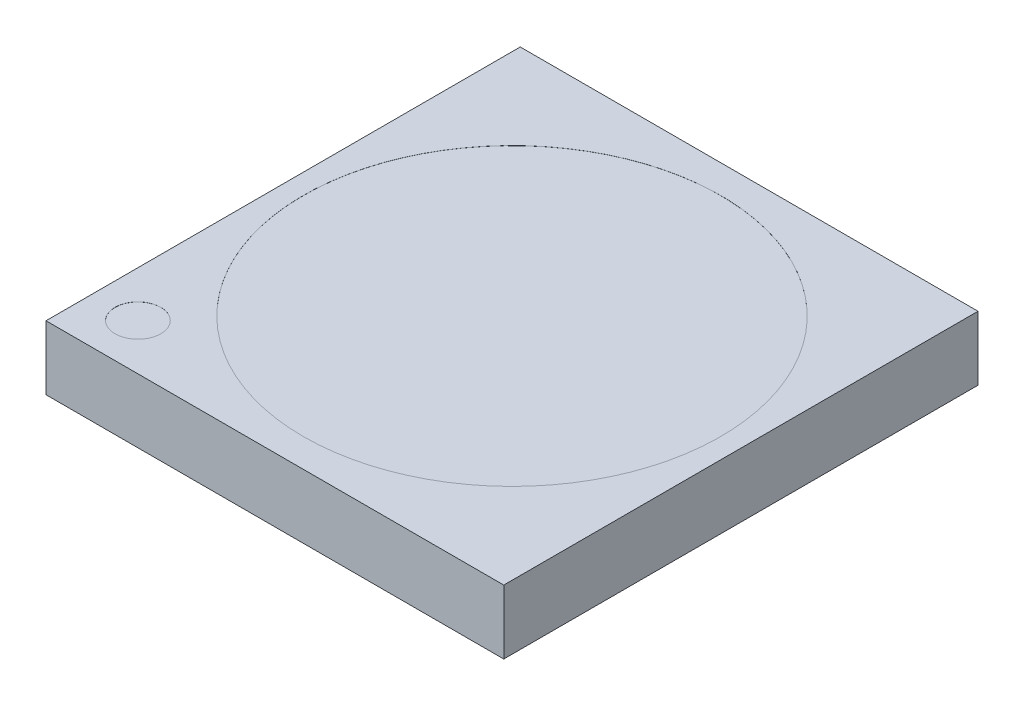
SolidWorks part; units mm, degrees
ref_plane "Alzado" through (0, 0, 0) normal (0, 0, 1) x (1, 0, 0)
ref_plane "Planta" through (0, 0, 0) normal (0, 1, 0) x (1, 0, 0)
ref_plane "Vista lateral" through (0, 0, 0) normal (1, 0, 0) x (0, 0, -1)
ref_plane "Plane1" through (0, 0, 0) normal (0, -1, 0) x (1, 0, 0)
sketch "Sketch1" plane through (0, 0, 0) normal (0, -1, 0) x (1, 0, 0)
  line L0 (2.5, 2.59) -> (-2.5, 2.59)
  line L1 (-2.5, 2.59) -> (-2.5, -2.59)
  line L2 (-2.5, -2.59) -> (2.5, -2.59)
  line L3 (2.5, -2.59) -> (2.5, 2.59)
extrude "Extrude1" add sketch "Sketch1" against normal blind 0.7
sketch "Sketch2" plane through (0, 0, 0) normal (0, -1, 0) x (1, 0, 0)
  line L0 (-0.3, 0.18) -> (-0.3, 2.27)
  line L1 (-0.3, 2.27) -> (-1.3472, 2.27)
  line L2 (-2.1, 1.4301) -> (-2.1, -1.4301)
  line L3 (-1.3472, -2.27) -> (-0.3, -2.27)
  line L4 (-0.3, -2.27) -> (-0.3, -0.18)
  arc A0 (-0.3, -0.18) -> (-0.3, 0.18) centre (-0.3, 0) cw
  arc A1 (-1.3472, 2.27) -> (-1.5249, 2.0616) centre (-1.3472, 2.09) ccw
  arc A2 (-1.5249, 2.0616) -> (-1.9168, 1.6101) centre (-1.91, 2) cw
  arc A3 (-1.9168, 1.6101) -> (-2.1, 1.4301) centre (-1.92, 1.4301) ccw
  arc A4 (-2.1, -1.4301) -> (-1.92, -1.6101) centre (-1.92, -1.4301) ccw
  arc A5 (-1.92, -1.6101) -> (-1.9168, -1.6101) centre (-1.92, -1.4301) ccw
  arc A6 (-1.9168, -1.6101) -> (-1.5249, -2.0616) centre (-1.91, -2) cw
  arc A7 (-1.5249, -2.0616) -> (-1.3472, -2.27) centre (-1.3472, -2.09) ccw
extrude "Extrude2" cut sketch "Sketch2" against normal blind 0.001
sketch "Sketch3" plane through (0, 0, 0) normal (0, -1, 0) x (1, 0, 0)
  line L0 (1.3472, 2.27) -> (0.3, 2.27)
  line L1 (0.3, 2.27) -> (0.3, -2.27)
  line L2 (0.3, -2.27) -> (1.3472, -2.27)
  line L3 (2.1, -1.4301) -> (2.1, 1.4301)
  arc A0 (1.9168, 1.6101) -> (1.5249, 2.0616) centre (1.91, 2) cw
  arc A1 (1.5249, 2.0616) -> (1.3472, 2.27) centre (1.3472, 2.09) ccw
  arc A2 (1.3472, -2.27) -> (1.5249, -2.0616) centre (1.3472, -2.09) ccw
  arc A3 (1.5249, -2.0616) -> (1.9168, -1.6101) centre (1.91, -2) cw
  arc A4 (1.9168, -1.6101) -> (1.92, -1.6101) centre (1.92, -1.4301) ccw
  arc A5 (1.92, -1.6101) -> (2.1, -1.4301) centre (1.92, -1.4301) ccw
  arc A6 (2.1, 1.4301) -> (1.9168, 1.6101) centre (1.92, 1.4301) ccw
extrude "Extrude3" cut sketch "Sketch3" against normal blind 0.001
ref_plane "Plane2" through (0, 0, 0) normal (0, 0, -1) x (-1, 0, 0)
sketch "Sketch4" plane through (0, 0, 0) normal (0, 0, -1) x (-1, 0, 0)
  line L0 (-2.28, 0.699) -> (0, 0.699)
  line L1 (0, 0.699) -> (0, 0.7)
  line L2 (0, 0.7) -> (-2.28, 0.7)
  line L3 (-2.28, 0.7) -> (-2.28, 0.699)
  line L4 (0, 0.699) -> (0, 0.7) construction
revolve "Cut-Revolve1" cut sketch "Sketch4" angle 360 about L4
ref_plane "Plane3" through (0, 0, 2.086) normal (0, 0, -1) x (-1, 0, 0)
sketch "Sketch5" plane through (0, 0, 2.086) normal (0, 0, -1) x (-1, 0, 0)
  line L0 (1.75, 0.699) -> (2, 0.699)
  line L1 (2, 0.699) -> (2, 0.7)
  line L2 (2, 0.7) -> (1.75, 0.7)
  line L3 (1.75, 0.7) -> (1.75, 0.699)
  line L4 (2, 0.699) -> (2, 0.7) construction
revolve "Cut-Revolve2" cut sketch "Sketch5" angle 360 about L4
fillet "Fillet1" radius 0.05 2 edges at (-0.3, 0.0005, -0.18) (-0.3, 0.0005, 0.18)
fillet "Fillet2" radius 0.5 4 edges at (-0.3, 0.0005, 2.27) (0.3, 0.0005, -2.27) (0.3, 0.0005, 2.27) (-0.3, 0.0005, -2.27)
